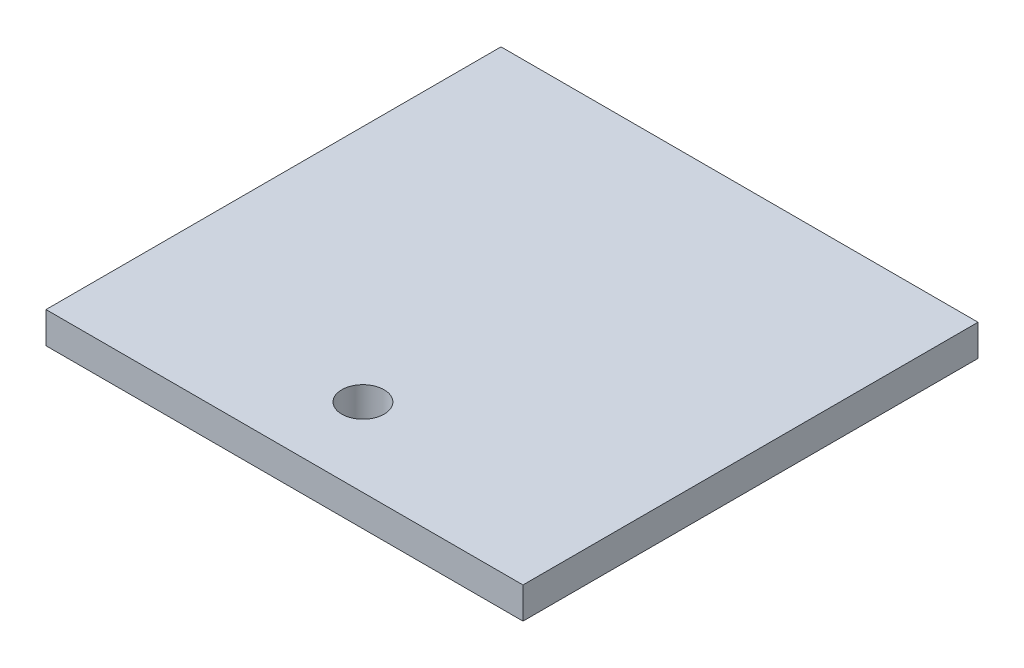
SolidWorks part; units mm, degrees
ref_plane "Front Plane" through (0, 0, 0) normal (0, 0, 1) x (1, 0, 0)
ref_plane "Top Plane" through (0, 0, 0) normal (0, 1, 0) x (1, 0, 0)
ref_plane "Right Plane" through (0, 0, 0) normal (1, 0, 0) x (0, 0, -1)
sketch "Sketch1" plane through (0, 0, 0) normal (0, 1, 0) x (1, 0, 0)
  line L1 (-76, -72.5) -> (76, -72.5)
  line L2 (-76, -72.5) -> (-76, 72.5)
  line L3 (-76, 72.5) -> (76, 72.5)
  line L4 (76, -72.5) -> (76, 72.5)
  line L5 (-76, -72.5) -> (76, 72.5) construction
  line L6 (-76, 72.5) -> (76, -72.5) construction
  point P0 (0, 0)
extrude "Boss-Extrude1" add sketch "Sketch1" along normal blind 10 contours L2 L3 L4 L1
sketch "Sketch2" plane through (0, 0, 0) normal (0, 1, 0) x (1, 0, 0)
  circle A0 centre (0, -47.5) radius 6.75
extrude "Cut-Extrude1" cut sketch "Sketch2" along normal blind 18
